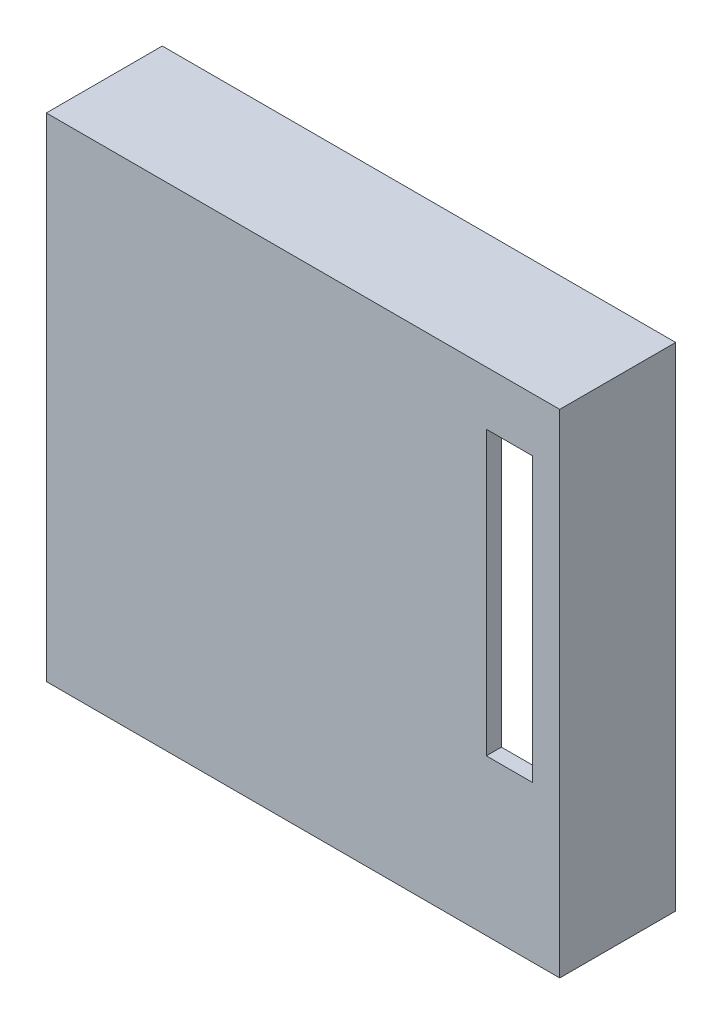
SolidWorks part; units mm, degrees
ref_plane "Front Plane" through (0, 0, 0) normal (0, 0, 1) x (1, 0, 0)
ref_plane "Top Plane" through (0, 0, 0) normal (0, 1, 0) x (1, 0, 0)
ref_plane "Right Plane" through (0, 0, 0) normal (1, 0, 0) x (0, 0, -1)
sketch "Sketch1" plane through (0, 2.1889, 0) normal (0, -1, 0) x (1, 0, 0)
  line L0 (-10.0866, 78.3903) -> (-12.9207, 78.3903)
  line L1 (-12.9207, 78.3903) -> (-12.9207, 101.4633)
  line L2 (-12.9207, 101.4633) -> (89.2476, 101.4633)
  line L3 (89.2476, 101.4633) -> (89.2476, 78.3903)
  line L4 (89.2476, 78.3903) -> (86.4134, 78.3903)
  line L5 (86.4134, 78.3903) -> (86.4134, 79.8903)
  line L6 (86.4134, 79.8903) -> (88.4215, 79.8903)
  line L7 (88.4215, 79.8903) -> (88.4215, 81.6903)
  line L8 (88.4215, 81.6903) -> (86.2476, 81.6903)
  line L9 (86.2476, 81.6903) -> (86.2476, 98.4633)
  line L10 (86.2476, 98.4633) -> (-9.9207, 98.4633)
  line L11 (-9.9207, 98.4633) -> (-9.9207, 81.6903)
  line L12 (-9.9207, 81.6903) -> (-12.0947, 81.6903)
  line L13 (-12.0947, 81.6903) -> (-12.0947, 79.8903)
  line L14 (-12.0947, 79.8903) -> (-10.0866, 79.8903)
  line L15 (-10.0866, 79.8903) -> (-10.0866, 78.3903)
  point P4 (-9.9207, 104.3314)
extrude "Boss-Extrude1" add sketch "Sketch1" against normal blind 95 and the other way blind 1
sketch "Sketch3" plane through (0, 97.1889, 0) normal (0, 1, 0) x (1, 0, 0)
  line L1 (89.2476, -101.4633) -> (-12.9207, -101.4633)
  line L2 (89.2476, -101.4633) -> (89.2476, -78.3903)
  line L3 (89.2476, -78.3903) -> (-12.9207, -78.3903)
  line L4 (-12.9207, -101.4633) -> (-12.9207, -78.3903)
extrude "Boss-Extrude2" add sketch "Sketch3" along normal blind 2
sketch "Sketch4" plane through (-12.9207, 0, 0) normal (-1, 0, 0) x (0, 0, 1)
  line L0 (78.3903, 1.1889) -> (78.3903, 99.1889) construction
  line L1 (78.3903, 11.4889) -> (82.3135, 11.4889)
  line L3 (78.3903, 82.3889) -> (82.3135, 82.3889)
  line L4 (82.3135, 11.4889) -> (82.3135, 82.3889)
  line L5 (76.7903, 2.1889) -> (61.7728, 2.1889) construction
  line L7 (76.7903, 93.1889) -> (61.7728, 93.1889) construction
  line L9 (78.3903, 82.3889) -> (75.7665, 82.3889)
  line L11 (78.3903, 11.4889) -> (75.7665, 11.4889)
  line L12 (75.7665, 82.3889) -> (75.7665, 11.4889)
  dimension "D1" = 9.3
  dimension "D2" = 10.8
extrude "Cut-Extrude1" cut sketch "Sketch4" against normal blind 7 contours L12 L11 L1 L4 L3 L9
sketch "Sketch5" plane through (0, 0, 101.4633) normal (0, 0, 1) x (1, 0, 0)
  line L1 (74.6402, 32.1747) -> (83.794, 32.1747)
  line L2 (74.6402, 32.1747) -> (74.6402, 88.4631)
  line L3 (74.6402, 88.4631) -> (83.794, 88.4631)
  line L4 (83.794, 32.1747) -> (83.794, 88.4631)
extrude "Cut-Extrude2" cut sketch "Sketch5" against normal blind 12
